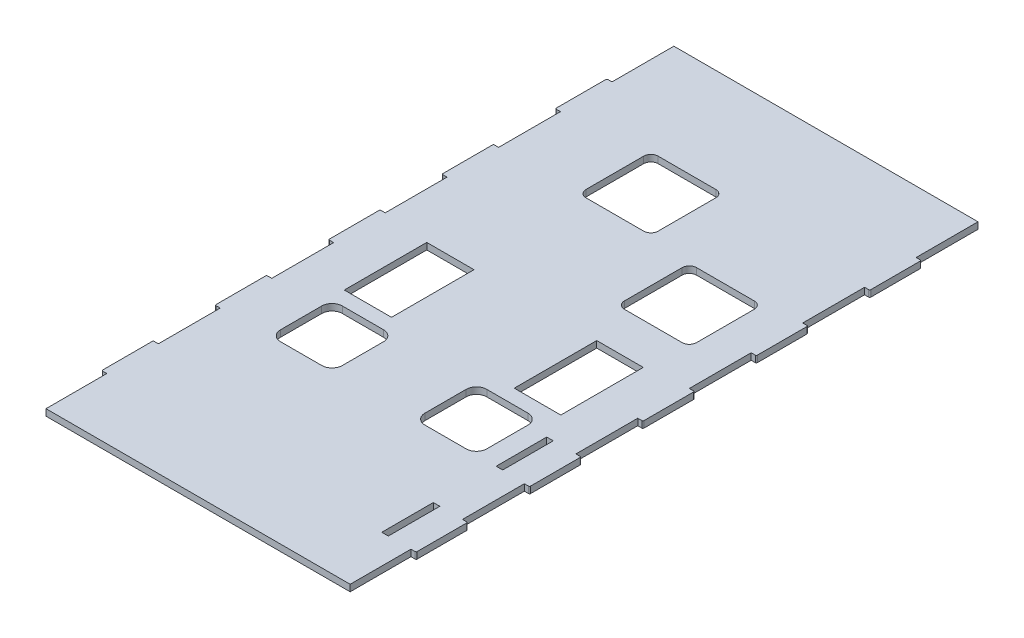
SolidWorks part; units mm, degrees
material "Oak"
ref_plane "Front Plane" through (0, 0, 0) normal (0, 0, 1) x (1, 0, 0)
ref_plane "Top Plane" through (0, 0, 0) normal (0, 1, 0) x (1, 0, 0)
ref_plane "Right Plane" through (0, 0, 0) normal (1, 0, 0) x (0, 0, -1)
sketch "Sketch1" plane through (0, 0, 0) normal (0, 1, 0) x (1, 0, 0)
  line L0 (157.0736, 348.6213) -> (157.0736, 288.6213)
  line L1 (-137.9264, 348.6213) -> (157.0736, 348.6213)
  line L3 (-137.9264, -260.3787) -> (157.0859, -260.3787)
  line L9 (157.0736, 288.6213) -> (162.0736, 288.6213)
  line L10 (162.0736, 288.6213) -> (162.0859, 238.6213)
  line L11 (162.0859, 238.6213) -> (157.0859, 238.6213)
  line L12 (157.0859, 238.6213) -> (157.0859, 178.6213)
  line L13 (157.0859, 178.6213) -> (162.0859, 178.6213)
  line L14 (162.0859, 178.6213) -> (162.0859, 128.6213)
  line L15 (162.0859, 128.6213) -> (157.0859, 128.6213)
  line L16 (157.0859, 128.6213) -> (157.0859, 68.6213)
  line L17 (157.0859, 68.6213) -> (162.0859, 68.6213)
  line L18 (162.0859, 68.6213) -> (162.0859, 18.6213)
  line L19 (162.0859, 18.6213) -> (157.0859, 18.6213)
  line L20 (157.0859, 18.6213) -> (157.0859, -41.3787)
  line L21 (157.0859, -41.3787) -> (162.0859, -41.3787)
  line L22 (162.0859, -41.3787) -> (162.0859, -91.3787)
  line L23 (162.0859, -91.3787) -> (157.0859, -91.3787)
  line L24 (157.0859, -91.3787) -> (157.0859, -151.3787)
  line L25 (157.0859, -151.3787) -> (162.0859, -151.3787)
  line L26 (162.0859, -151.3787) -> (162.0859, -201.3787)
  line L27 (162.0859, -201.3787) -> (157.0859, -201.3787)
  line L28 (157.0859, -201.3787) -> (157.0859, -260.3787)
  line L29 (-137.9264, 348.6213) -> (-137.9264, 288.6213)
  line L30 (-137.9264, 288.6213) -> (-142.9387, 288.6213)
  line L31 (-142.9387, 288.6213) -> (-142.9387, 238.6213)
  line L32 (-142.9387, 238.6213) -> (-137.9264, 238.6213)
  line L33 (-137.9264, 238.6213) -> (-137.9264, 178.6213)
  line L34 (-137.9264, 178.6213) -> (-142.9387, 178.6213)
  line L35 (-142.9387, 178.6213) -> (-142.9387, 128.6213)
  line L36 (-142.9387, 128.6213) -> (-137.9264, 128.6213)
  line L37 (-137.9264, 128.6213) -> (-137.9264, 68.6213)
  line L38 (-137.9264, 68.6213) -> (-142.9387, 68.6213)
  line L39 (-142.9387, 68.6213) -> (-142.9387, 18.6213)
  line L40 (-142.9387, 18.6213) -> (-137.9264, 18.6213)
  line L41 (-137.9264, 18.6213) -> (-137.9264, -41.3787)
  line L42 (-137.9264, -41.3787) -> (-142.9264, -41.3787)
  line L43 (-142.9264, -41.3787) -> (-142.9264, -91.3787)
  line L44 (-142.9264, -91.3787) -> (-137.9264, -91.3787)
  line L45 (-137.9264, -91.3787) -> (-137.9264, -151.3787)
  line L46 (-137.9264, -151.3787) -> (-142.9387, -151.3787)
  line L47 (-142.9387, -151.3787) -> (-142.9387, -201.3787)
  line L48 (-142.9387, -201.3787) -> (-137.9264, -201.3787)
  line L49 (-137.9264, -201.3787) -> (-137.9264, -260.3787)
  line L50 (128.7359, -259.5286) -> (128.7359, -159.5286) construction
  line L51 (128.7359, -159.5286) -> (-137.9141, -110.3787) construction
  line L52 (-137.9141, -110.3787) -> (-137.9141, -60.3787) construction
  line L53 (-137.9141, -60.3787) -> (162.0859, -60.3787) construction
  line L55 (-80.4688, -30.3787) -> (-40.4688, -30.3787)
  line L56 (-90.4688, -40.3787) -> (-90.4688, -80.3787)
  line L57 (-80.4688, -90.3787) -> (-40.4688, -90.3787)
  line L58 (-30.4688, -40.3787) -> (-30.4688, -80.3787)
  line L59 (-90.4688, -30.3787) -> (-30.4688, -90.3787) construction
  line L60 (-90.4688, -90.3787) -> (-30.4688, -30.3787) construction
  line L61 (59.5859, -30.3787) -> (99.5859, -30.3787)
  line L62 (49.5859, -40.3787) -> (49.5859, -80.3787)
  line L63 (59.5859, -90.3787) -> (99.5859, -90.3787)
  line L64 (109.5859, -40.3787) -> (109.5859, -80.3787)
  line L65 (49.5859, -30.3787) -> (109.5859, -90.3787) construction
  line L66 (49.5859, -90.3787) -> (109.5859, -30.3787) construction
  line L67 (128.7359, -201.3787) -> (135.0859, -201.3787)
  line L68 (128.7359, -201.3787) -> (128.7359, -151.3787)
  line L69 (128.7359, -151.3787) -> (135.0859, -151.3787)
  line L70 (135.0859, -201.3787) -> (135.0859, -151.3787)
  line L71 (128.7359, -90.3787) -> (135.0859, -90.3787)
  line L72 (128.7359, -90.3787) -> (128.7359, -41.3787)
  line L73 (128.7359, -41.3787) -> (135.0859, -41.3787)
  line L74 (135.0859, -90.3787) -> (135.0859, -41.3787)
  line L75 (-53.198, 248.6213) -> (2.802, 248.6213)
  line L76 (-60.198, 241.6213) -> (-60.198, 185.6213)
  line L77 (-53.198, 178.6213) -> (2.802, 178.6213)
  line L78 (9.802, 241.6213) -> (9.802, 185.6213)
  line L83 (59.0859, 173.6213) -> (115.0859, 173.6213)
  line L84 (52.0859, 166.6213) -> (52.0859, 110.6213)
  line L85 (59.0859, 103.6213) -> (115.0859, 103.6213)
  line L86 (122.0859, 166.6213) -> (122.0859, 110.6213)
  line L87 (-92.9264, 63.9367) -> (-47.1008, 63.9367)
  line L88 (-92.9264, 63.9367) -> (-92.9264, -16.0633)
  line L89 (-92.9264, -16.0633) -> (-47.1008, -16.0633)
  line L90 (-47.1008, 63.9367) -> (-47.1008, -16.0633)
  line L91 (71.9462, 63.9367) -> (117.0859, 63.9367)
  line L92 (71.9462, 63.9367) -> (71.9462, -16.0633)
  line L93 (71.9462, -16.0633) -> (117.0859, -16.0633)
  line L94 (117.0859, 63.9367) -> (117.0859, -16.0633)
  arc A0 (99.5859, -30.3787) -> (109.5859, -40.3787) centre (99.5859, -40.3787) cw
  arc A1 (109.5859, -80.3787) -> (99.5859, -90.3787) centre (99.5859, -80.3787) cw
  arc A2 (59.5859, -90.3787) -> (49.5859, -80.3787) centre (59.5859, -80.3787) cw
  arc A3 (49.5859, -40.3787) -> (59.5859, -30.3787) centre (59.5859, -40.3787) cw
  arc A4 (-90.4688, -80.3787) -> (-80.4688, -90.3787) centre (-80.4688, -80.3787) ccw
  arc A5 (-40.4688, -90.3787) -> (-30.4688, -80.3787) centre (-40.4688, -80.3787) ccw
  arc A6 (-40.4688, -30.3787) -> (-30.4688, -40.3787) centre (-40.4688, -40.3787) cw
  arc A7 (-80.4688, -30.3787) -> (-90.4688, -40.3787) centre (-80.4688, -40.3787) ccw
  arc A12 (2.802, 248.6213) -> (9.802, 241.6213) centre (2.802, 241.6213) cw
  arc A13 (9.802, 185.6213) -> (2.802, 178.6213) centre (2.802, 185.6213) cw
  arc A14 (-53.198, 178.6213) -> (-60.198, 185.6213) centre (-53.198, 185.6213) cw
  arc A15 (-60.198, 241.6213) -> (-53.198, 248.6213) centre (-53.198, 241.6213) cw
  arc A16 (115.0859, 173.6213) -> (122.0859, 166.6213) centre (115.0859, 166.6213) cw
  arc A17 (122.0859, 110.6213) -> (115.0859, 103.6213) centre (115.0859, 110.6213) cw
  arc A18 (59.0859, 103.6213) -> (52.0859, 110.6213) centre (59.0859, 110.6213) cw
  arc A19 (52.0859, 166.6213) -> (59.0859, 173.6213) centre (59.0859, 166.6213) cw
  point P46 (-90.4141, -60.3787)
  point P54 (61.387, -60.3787)
  point P97 (122.0859, 173.6213)
  point P107 (52.0859, 103.6213)
  point P110 (52.0859, 173.6213)
  point P114 (9.802, 248.6213)
  point P119 (-60.198, 178.6213)
  point P122 (-60.198, 248.6213)
  dimension "D29" = 10
  dimension "D38" = 175
  dimension "D37" = 7
  dimension "D1" = 295
  dimension "D2" = 609
  dimension "D3" = 60
  dimension "D4" = 5
  dimension "D5" = 50
  dimension "D6" = 60
  dimension "D7" = 50
  dimension "D8" = 60
  dimension "D9" = 50
  dimension "D10" = 60
  dimension "D11" = 50
  dimension "D12" = 60
  dimension "D13" = 59
  dimension "D14" = 50
  dimension "D15" = 5
  dimension "D16" = 5
  dimension "D17" = 28.35
  dimension "D18" = 100
  dimension "D19" = 150
  dimension "D20" = 50
  dimension "D21" = 47.5
  dimension "D22" = 60
  dimension "D23" = 60
  dimension "D24" = 30
  dimension "D25" = 60
  dimension "D26" = 60
  dimension "D27" = 30
  dimension "D28" = 47.5
  dimension "D30" = 6.35
  dimension "D31" = 6.35
  dimension "D32" = 70
  dimension "D33" = 70
  dimension "D34" = 70
  dimension "D35" = 70
  dimension "D36" = 100
  dimension "D39" = 80
  dimension "D40" = 80
  dimension "D41" = 40
  dimension "D42" = 35
  dimension "D43" = 45
extrude "Boss-Extrude1" add sketch "Sketch1" along normal blind 6.35 contours L3 L28 L27 L26 L25 L24 L23 L22 L21 L20 L19 L18 L17 L16 L15 L14 L13 L12 L11 L10 L9 L0 L1 L29 L30 L31 L32 L33 L34 L35 L36 L37 L38 L39 L40 L41 L42 L43 L44 L45 L46 L47 L48 L49
fillet "Fillet1" radius 1 20 edges at (-142.9387, 3.175, -288.6213) (-142.9387, 3.175, -238.6213) (-142.9387, 3.175, -178.6213) (-142.9387, 3.175, -128.6213) (-142.9387, 3.175, -68.6213) (-142.9387, 3.175, -18.6213) (-142.9264, 3.175, 41.3787) (-142.9264, 3.175, 91.3787) (-142.9387, 3.175, 201.3787) (162.0736, 3.175, -288.6213) (162.0859, 3.175, -238.6213) (162.0859, 3.175, -178.6213) (162.0859, 3.175, -128.6213) (162.0859, 3.175, -68.6213) (162.0859, 3.175, -18.6213) (162.0859, 3.175, 41.3787) (162.0859, 3.175, 91.3787) (162.0859, 3.175, 151.3787) (162.0859, 3.175, 201.3787) (-142.9387, 3.175, 151.3787)
